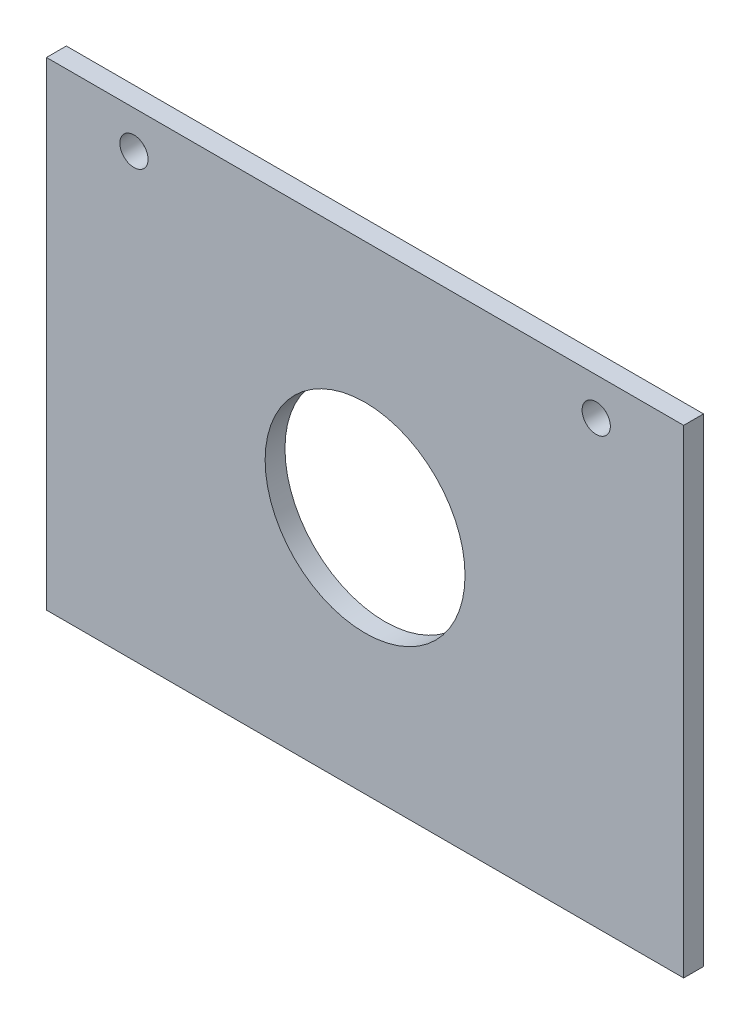
SolidWorks part; units mm, degrees
ref_plane "Front Plane" through (0, 0, 0) normal (0, 0, 1) x (1, 0, 0)
ref_plane "Top Plane" through (0, 0, 0) normal (0, 1, 0) x (1, 0, 0)
ref_plane "Right Plane" through (0, 0, 0) normal (1, 0, 0) x (0, 0, -1)
sketch "Sketch1" plane through (0, 0, 0) normal (0, 0, 1) x (1, 0, 0)
  line L0 (25.5, 38.31) -> (25.5, 0) construction
  line L1 (0, 38.31) -> (51, 38.31)
  line L2 (0, 38.31) -> (0, 0)
  line L3 (0, 0) -> (51, 0)
  line L4 (51, 38.31) -> (51, 0)
  circle A0 centre (25.5, 19.155) radius 8
  dimension "D3" = 16
  dimension "D1" = 38.31
  dimension "D2" = 51
extrude "Boss-Extrude1" add sketch "Sketch1" along normal blind 1.5875
sketch "Sketch2" plane through (0, 0, 1.5875) normal (0, 0, 1) x (1, 0, 0)
  line L0 (7, 35.31) -> (44, 35.31) construction
  line L1 (25.5, 38.31) -> (25.5, 35.31) construction
  line L2 (51, 38.31) -> (0, 38.31) construction
  circle A0 centre (44, 35.31) radius 1.1303
  circle A1 centre (7, 35.31) radius 1.1303
  dimension "D2" = 2.2606
  dimension "D3" = 3
  dimension "D1" = 37
extrude "Cut-Extrude1" cut sketch "Sketch2" against normal up to surface (1.5875 mm away) up to face at (25.5, 19.155, 0)
